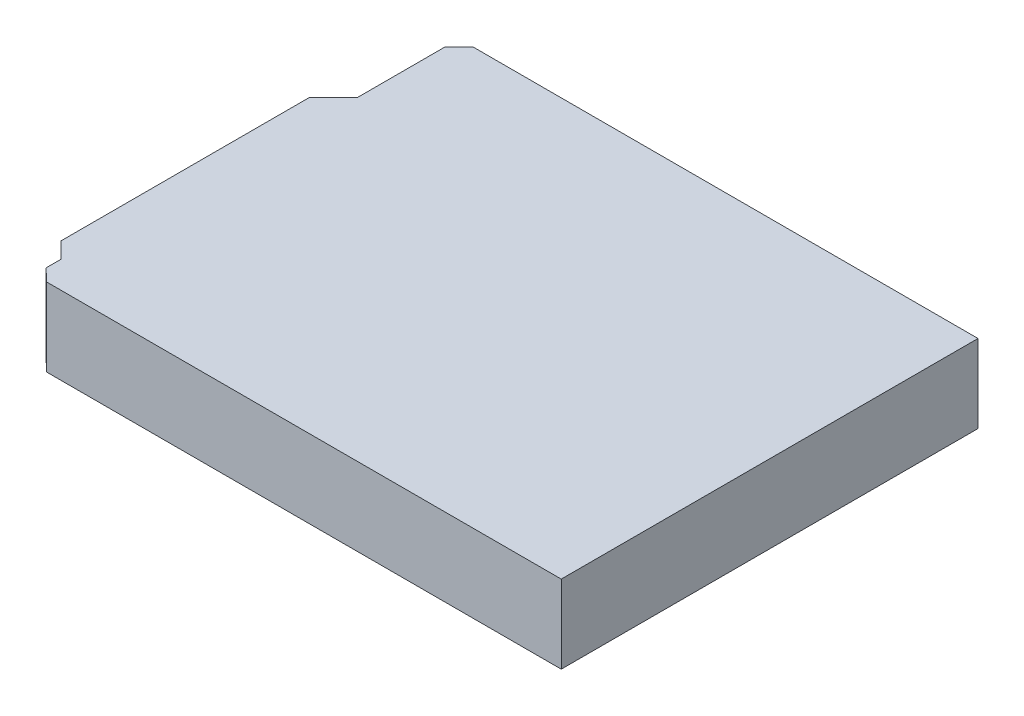
SolidWorks part; units mm, degrees
ref_plane "Front Plane" through (0, 0, 0) normal (0, 0, 1) x (1, 0, 0)
ref_plane "Top Plane" through (0, 0, 0) normal (0, 1, 0) x (1, 0, 0)
ref_plane "Right Plane" through (0, 0, 0) normal (1, 0, 0) x (0, 0, -1)
sketch "Sketch1" plane through (0, 0, 0) normal (0, 1, 0) x (1, 0, 0)
  line L0 (-28.5912, 26.2585) -> (-30.359, 24.4907)
  line L1 (-30.359, 24.4907) -> (-30.359, 13.2607)
  line L2 (-30.359, 13.2607) -> (-33.4419, 10.1778)
  line L3 (-33.4419, 10.1778) -> (-33.4419, -21.6522)
  line L4 (-33.4419, -21.6522) -> (-31.4014, -23.6928)
  line L5 (-31.4014, -23.6928) -> (-31.4014, -25.6228)
  line L6 (-31.4014, -25.6228) -> (-29.7912, -27.1415)
  line L7 (-29.7912, -27.1415) -> (36.1388, -27.1415)
  line L8 (36.1388, -27.1415) -> (36.1388, 26.2585)
  line L9 (36.1388, 26.2585) -> (-28.5912, 26.2585)
  point P7 (-30.7203, -26.4701)
  point P11 (0, 0)
  point P12 (0, 0)
  point P13 (0, 0)
  point P14 (-31.4014, -25.2232)
  dimension "D1" = 64.73
  dimension "D2" = 53.4
  dimension "D3" = 65.93
  dimension "D4" = 11.23
  dimension "D5" = 31.83
  dimension "D6" = 2.5
  dimension "D7" = 4.36
  dimension "D8" = 3.083
  dimension "D9" = 2.8857
  dimension "D10" = 135
  dimension "D11" = 1.93
extrude "Boss-Extrude1" add sketch "Sketch1" along normal blind 10
